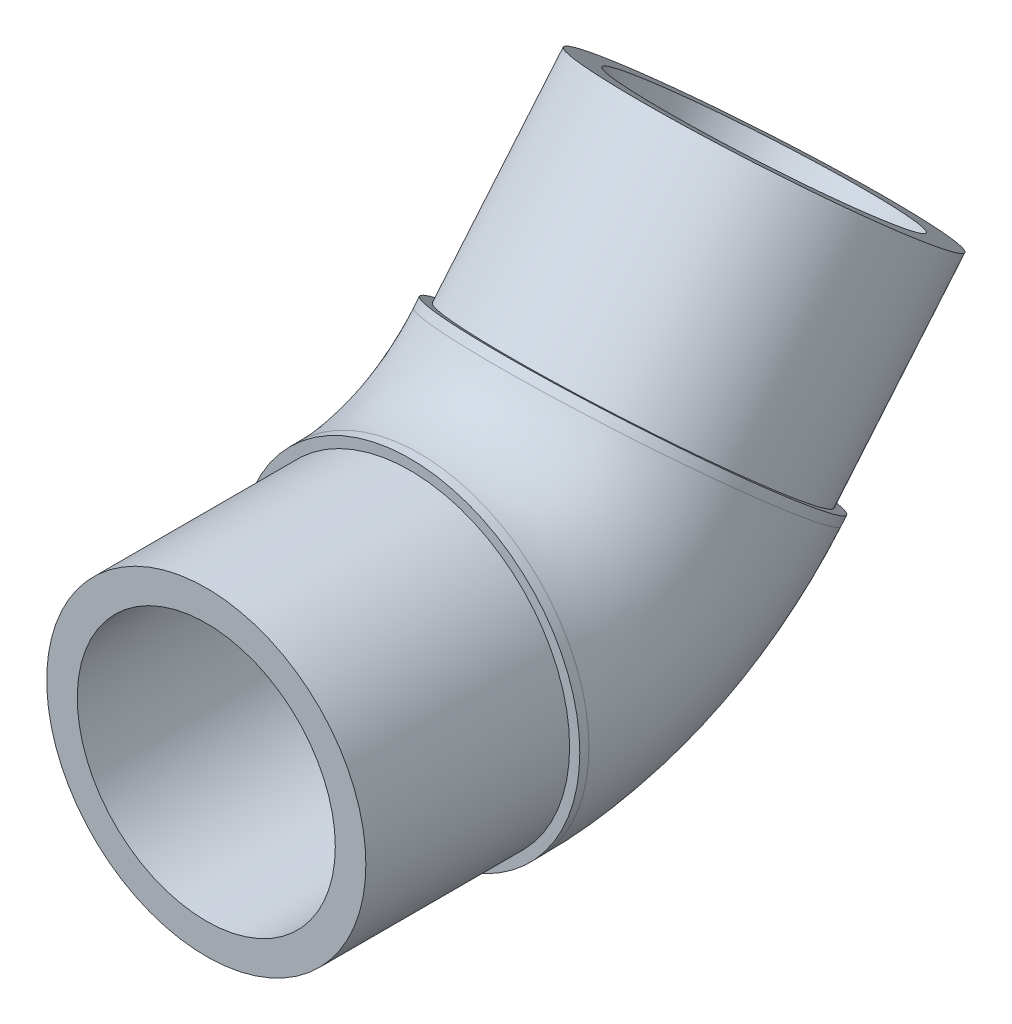
SolidWorks part; units mm, degrees
ref_plane "Plan de face" through (0, 0, 0) normal (0, 0, 1) x (1, 0, 0)
ref_plane "Plan de dessus" through (0, 0, 0) normal (0, 1, 0) x (1, 0, 0)
ref_plane "Plan de droite" through (0, 0, 0) normal (1, 0, 0) x (0, 0, -1)
sketch "Esquisse1" plane through (0, 0, 0) normal (0, 0, 1) x (1, 0, 0)
  circle A0 centre (0, 0) radius 19
  circle A1 centre (0, 0) radius 25
  dimension "D1" = 50
  dimension "D2" = 6
sketch "Esquisse2" plane through (0, 0, 0) normal (1, 0, 0) x (0, 0, -1)
  line L0 (0, 0) -> (31.3477, 0)
  line L1 (61.9895, 14.2885) -> (82.1394, 38.3022)
  arc A0 (31.3477, 0) -> (61.9895, 14.2885) centre (31.3477, 40) ccw
  point P6 (50, 0)
  dimension "D4" = 40
  dimension "D1" = 130
  dimension "D2" = 50
  dimension "D3" = 50
sweep "Balayage1" add profiles "Esquisse1" path "Esquisse2"
sketch "Esquisse3" plane through (0, 0, 0) normal (0, 0, 1) x (1, 0, 0)
  circle A0 centre (0, 0) radius 23.5
  circle A1 centre (0, 0) radius 27.5
  dimension "D1" = 47
  dimension "D2" = 55
extrude "Enlèv. mat.-Extru.1" cut sketch "Esquisse3" against normal blind 30
sketch "Esquisse4" plane through (0, 62.9224, -52.7982) normal (0, 0.766, -0.6428) x (1, 0, 0)
  circle A2 centre (0, 38.3022) radius 23.5
  circle A3 centre (0, 38.3022) radius 27.5
  circle A4 centre (0, 38.3022) radius 25 construction
  dimension "D1" = 47
  dimension "D2" = 55
extrude "Enlèv. mat.-Extru.2" cut sketch "Esquisse4" against normal blind 30
